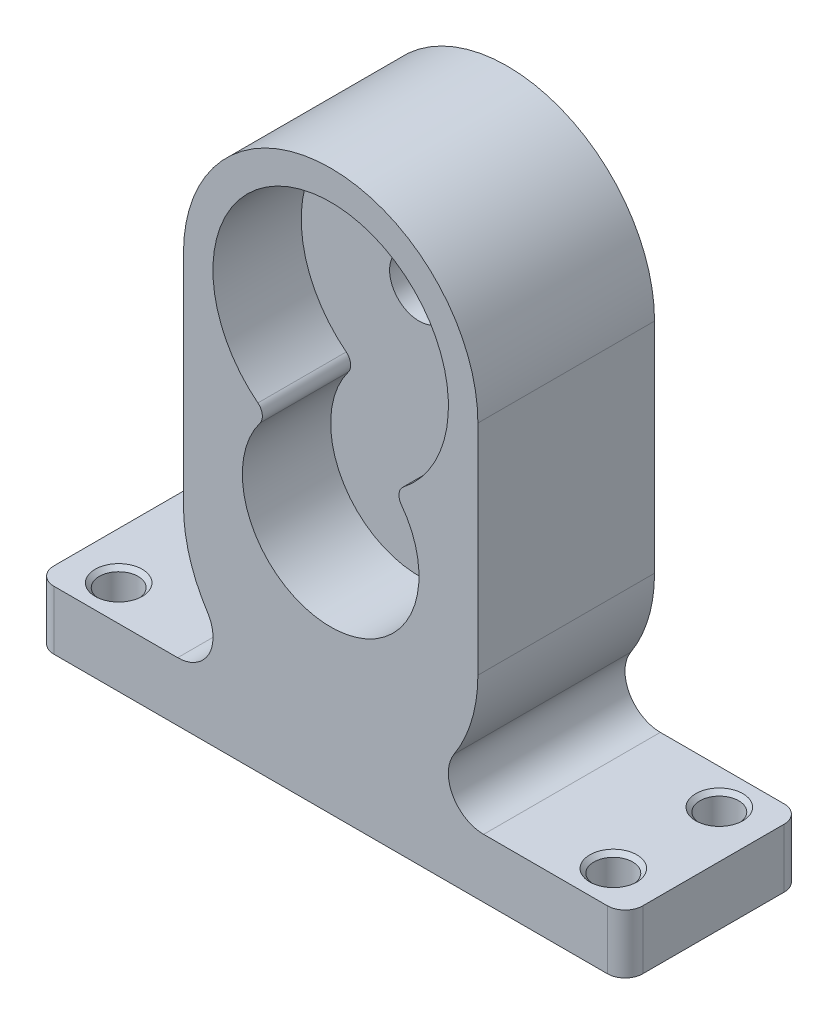
SolidWorks part; units mm, degrees
ref_plane "Спереди" through (0, 0, 0) normal (0, 0, 1) x (1, 0, 0)
ref_plane "Сверху" through (0, 0, 0) normal (0, 1, 0) x (1, 0, 0)
ref_plane "Справа" through (0, 0, 0) normal (1, 0, 0) x (0, 0, -1)
sketch "Эскиз1" plane through (0, 0, 0) normal (0, 0, 1) x (1, 0, 0)
  line L0 (0, 0) -> (0, 70)
  line L1 (0, 95) -> (0, 70)
  line L2 (25, 70) -> (25, 32.9129)
  line L3 (10, 10) -> (50, 10)
  line L4 (50, 10) -> (50, 0)
  line L5 (0, 0) -> (50, 0)
  arc A0 (25, 70) -> (0, 95) centre (0, 70) ccw
  arc A1 (25, 32.9129) -> (10, 10) centre (0, 32.9129) cw
  point P9 (0, 0)
  point P10 (0, 0)
  dimension "D1" = 25
  dimension "D2" = 70
  dimension "D3" = 10
  dimension "D4" = 10
  dimension "D5" = 50
extrude "Бобышка-Вытянуть1" add sketch "Эскиз1" against normal blind 30
mirror "Зеркальное отражение1" about plane through (0, 0, 0) normal (1, 0, 0) of "Бобышка-Вытянуть1"
fillet "Скругление3" radius 6 1 edges at (10, 10, -15)
fillet "Скругление4" radius 6 1 edges at (-10, 10, -15)
sketch "Эскиз2" plane through (0, 0, 0) normal (0, 0, 1) x (1, 0, 0)
  circle A0 centre (0, 70) radius 20
  arc A2 (25, 70) -> (-25, 70) centre (0, 70) ccw construction
  dimension "D1" = 40
extrude "Вырез-Вытянуть1" cut sketch "Эскиз2" against normal blind 15
sketch "Эскиз3" plane through (0, 0, 0) normal (0, 0, 1) x (1, 0, 0)
  circle A0 centre (0, 70) radius 5
  arc A1 (25, 70) -> (-25, 70) centre (0, 70) ccw construction
  dimension "D1" = 10
extrude "Вырез-Вытянуть2" cut sketch "Эскиз3" against normal through all
sketch "Эскиз4" plane through (0, 0, 0) normal (0, 0, 1) x (1, 0, 0)
  circle A0 centre (0, 42.5) radius 15
  point P2 (0, 0)
  dimension "D1" = 30
  dimension "D2" = 42.5
extrude "Вырез-Вытянуть3" cut sketch "Эскиз4" against normal blind 15
fillet "Скругление5" radius 2 2 edges at (10.6449, 53.0682, -7.5) (-10.6449, 53.0682, -7.5)
sketch "Эскиз5" plane through (0, 10, 0) normal (0, 1, 0) x (1, 0, 0)
  line L0 (50, 30) -> (50, 0) construction
  line L2 (50, 30) -> (25.9799, 30) construction
  point P0 (42, 24)
  point P5 (43.1055, 25)
  dimension "D1" = 8
  dimension "D2" = 6
hole_wizard "Зенковка для винта с полупотайной головкой M61" positions "Эскиз6" profile "Эскиз7" countersink size "M6" standard "ISO" end condition through all
sketch "Эскиз6" plane through (0, 10, 0) normal (0, 1, 0) x (1, 0, 0)
  point P0 (42, 24)
sketch "Эскиз7" plane through (42, 10, -24) normal (1, 0, 0) x (0, 0, 1)
  line L0 (0, 0) -> (0, 10)
  line L1 (0, 10) -> (3.3, 10)
  line L2 (3.3, 10) -> (3.3, 0.7)
  line L3 (3.3, 0.7) -> (4, 0)
  line L5 (4, 0) -> (0, 0)
  line L6 (-3.3, 0.7) -> (-4, 0) construction
  line L11 (0, -6.35) -> (0, 107.95) construction
  dimension "Диаметр сквозного отверстия" = 6.6
  dimension "Глубина сквозного отверстия" = 10
  dimension "Диаметр передней зенковки" = 8
  dimension "Угол передней зенковки" = 90
pattern_linear "Линейный массив2" count 2 spacing 18 along (0, 0, 1) count 2 spacing 84 along (-1, 0, 0) of "Зенковка для винта с полупотайной головкой M61"
fillet "Скругление6" radius 3 4 edges at (-50, 5, 0) (-50, 5, -30) (50, 5, -30) (50, 5, 0)
